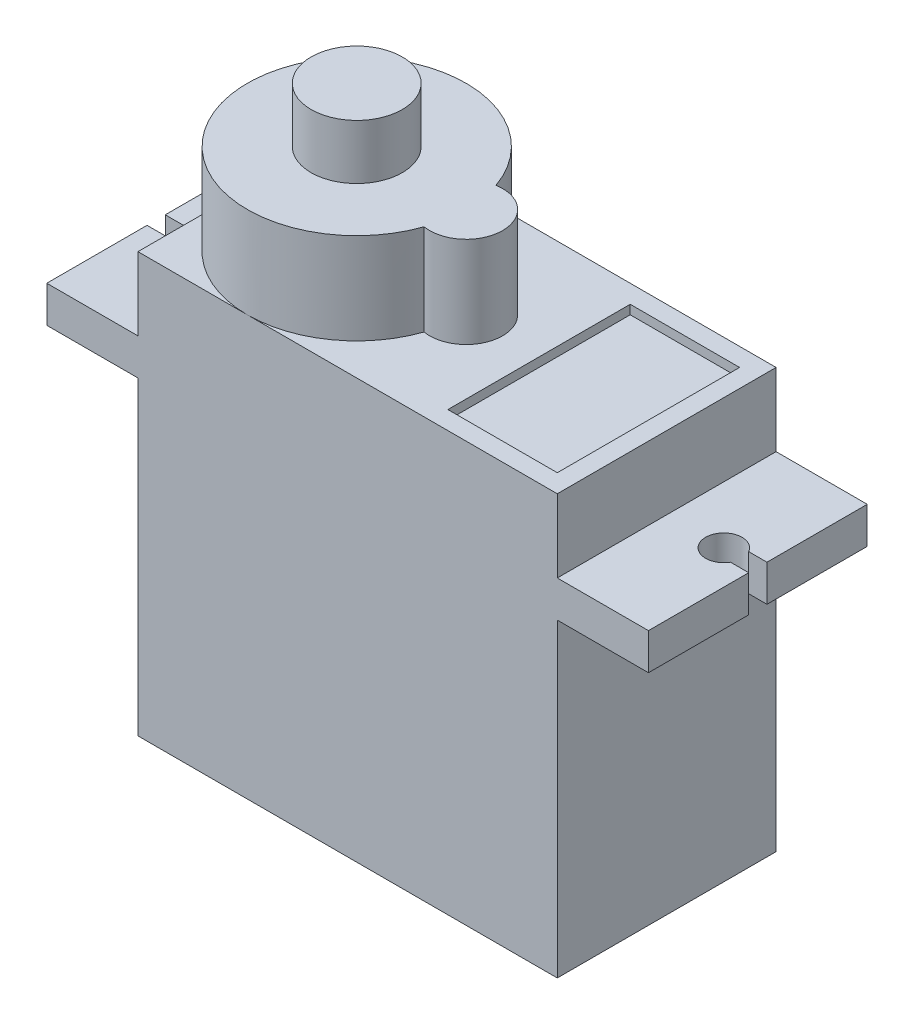
SolidWorks part; units mm, degrees
ref_plane "Front Plane" through (0, 0, 0) normal (0, 0, 1) x (1, 0, 0)
ref_plane "Top Plane" through (0, 0, 0) normal (0, 1, 0) x (1, 0, 0)
ref_plane "Right Plane" through (0, 0, 0) normal (1, 0, 0) x (0, 0, -1)
sketch "Sketch1" plane through (0, 0, 0) normal (0, 1, 0) x (1, 0, 0)
  line L1 (0, 0) -> (23, 0)
  line L2 (0, 0) -> (0, 12)
  line L3 (0, 12) -> (23, 12)
  line L4 (23, 0) -> (23, 12)
  dimension "D1" = 23
  dimension "D2" = 12
extrude "Boss-Extrude1" add sketch "Sketch1" along normal blind 23
sketch "Sketch2" plane through (0, 23, 0) normal (0, 1, 0) x (1, 0, 0)
  line L0 (23, 12) -> (0, 12) construction
  line L1 (0, 12) -> (0, 0) construction
  line L2 (0, 0) -> (23, 0) construction
  arc A0 (11.6667, 7.972) -> (11.6667, 4.028) centre (6, 6) ccw
  arc A1 (11.6667, 4.028) -> (11.6667, 7.972) centre (12, 6) ccw
  point P6 (12.9645, 6)
  point P11 (13.1171, 4.3932)
  point P12 (0, 0)
  dimension "D1" = 4
extrude "Boss-Extrude2" add sketch "Sketch2" along normal blind 5
sketch "Sketch3" plane through (23, 0, 0) normal (1, 0, 0) x (0, 0, -1)
  line L0 (0, 23) -> (0, 0) construction
  line L1 (0, 19) -> (12, 19)
  line L2 (0, 19) -> (0, 17)
  line L3 (0, 17) -> (12, 17)
  line L4 (12, 19) -> (12, 17)
  line L5 (12, 23) -> (12, 0) construction
  line L6 (0, 23) -> (12, 23) construction
  point P10 (6, 17)
  dimension "D1" = 4
  dimension "D2" = 2
extrude "Boss-Extrude3" add sketch "Sketch3" along normal blind 5
sketch "Sketch4" plane through (0, 19, 0) normal (0, 1, 0) x (1, 0, 0)
  line L0 (28, 12) -> (28, 0) construction
  line L1 (28, 6.5) -> (27, 6.5)
  line L2 (28, 5.5) -> (27, 5.5)
  line L3 (28, 6.5) -> (28, 5.5)
  line L4 (23, 12) -> (23, 0) construction
  arc A0 (27, 6.5) -> (27, 5.5) centre (26.134, 6) ccw
  point P5 (28, 6)
  dimension "D1" = 2
  dimension "D2" = 1
  dimension "D3" = 1
extrude "Cut-Extrude1" cut sketch "Sketch4" against normal blind 5 and the other way through all
ref_plane "Plane1" through (11.5, 0, 0) normal (-1, 0, 0) x (0, 0, 1)
mirror "Mirror3" about plane through (11.5, 0, 0) normal (-1, 0, 0) of "Cut-Extrude1", "Boss-Extrude3"
sketch "Sketch5" plane through (0, 28, 0) normal (0, 1, 0) x (1, 0, 0)
  circle A0 centre (6, 6) radius 2.5
  arc A1 (11.6667, 7.972) -> (11.6667, 4.028) centre (6, 6) ccw construction
  dimension "D1" = 5
extrude "Boss-Extrude4" add sketch "Sketch5" along normal blind 3
sketch "Sketch6" plane through (0, 23, 0) normal (0, 1, 0) x (1, 0, 0)
  line L0 (23, 12) -> (23, 0) construction
  line L1 (16, 11) -> (22, 11)
  line L2 (16, 11) -> (16, 1)
  line L3 (16, 1) -> (22, 1)
  line L4 (22, 11) -> (22, 1)
  line L5 (23, 12) -> (6, 12) construction
  line L6 (6, 0) -> (23, 0) construction
  dimension "D1" = 6
  dimension "D2" = 1
  dimension "D3" = 1
  dimension "D4" = 1
extrude "Cut-Extrude2" cut sketch "Sketch6" against normal blind 0.5
sketch "Sketch7" plane through (0, 0, 0) normal (-1, 0, 0) x (0, 0, 1)
  line L0 (-12, 0) -> (0, 0) construction
  line L1 (-7.5, 6) -> (-4.5, 6)
  line L2 (-7.5, 6) -> (-7.5, 5)
  line L3 (-7.5, 5) -> (-4.5, 5)
  line L4 (-4.5, 6) -> (-4.5, 5)
  line L5 (-12, 0) -> (0, 0) construction
  point P10 (-6, 0)
  point P11 (-6, 6)
  dimension "D1" = 6
  dimension "D2" = 3
  dimension "D3" = 1
extrude "Cut-Extrude3" cut sketch "Sketch7" against normal blind 1
